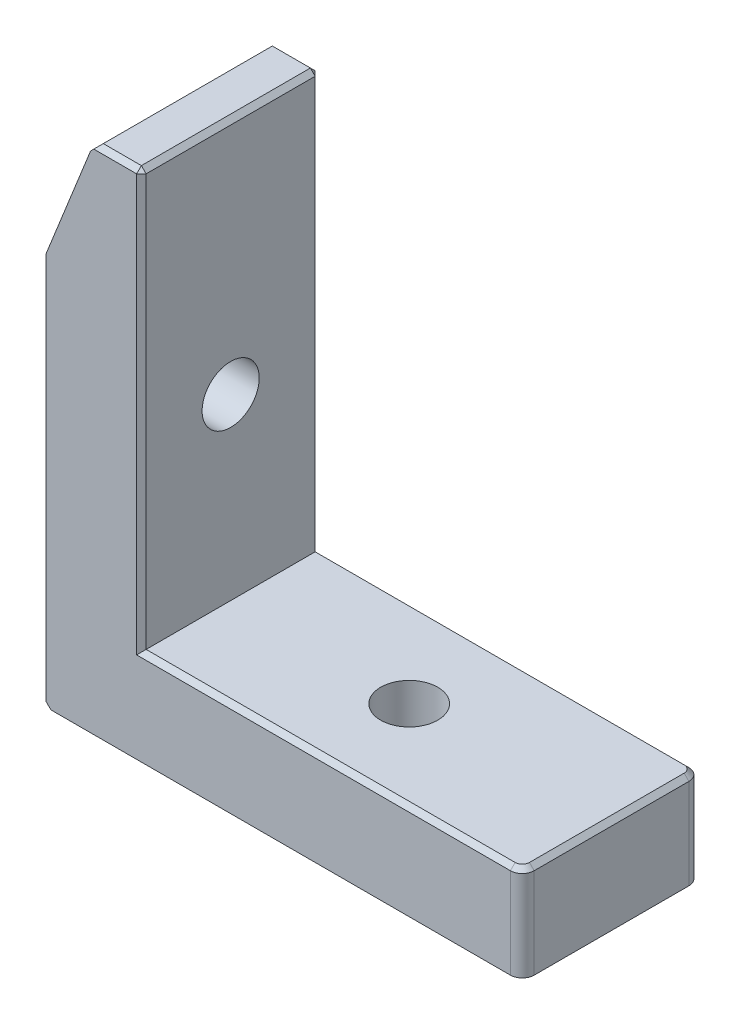
SolidWorks part; units mm, degrees
material "ABS"
ref_plane "Front Plane" through (0, 0, 0) normal (0, 0, 1) x (1, 0, 0)
ref_plane "Top Plane" through (0, 0, 0) normal (0, 1, 0) x (1, 0, 0)
ref_plane "Right Plane" through (0, 0, 0) normal (1, 0, 0) x (0, 0, -1)
sketch "Sketch1" plane through (0, 0, 0) normal (0, 0, 1) x (1, 0, 0)
  line L0 (0, 0) -> (0, 33)
  line L3 (4, 43) -> (8, 43)
  line L4 (8, 43) -> (8, 8)
  line L5 (8, 8) -> (40, 8)
  line L6 (40, 8) -> (40, 0)
  line L7 (40, 0) -> (0, 0)
  line L8 (0, 33) -> (4, 43)
  dimension "D1" = 35
  dimension "D2" = 8
  dimension "D3" = 4
  dimension "D4" = 8
  dimension "D5" = 40
  dimension "D6" = 10
extrude "Boss-Extrude1" add sketch "Sketch1" along normal mid plane 15
hole_wizard "CSK for M4 Hex Socket Countersunk Head Screw1" positions "Sketch2" profile "Sketch3" countersink size "M4" standard "DIN" end condition up to next
sketch "Sketch2" plane through (0, 0, 0) normal (0, -1, 0) x (-1, 0, 0)
  line L0 (-8, -7.5) -> (-8, 7.5) construction
  line L1 (0, 0) -> (-23, 0) construction
  line L2 (0, -7.5) -> (0, 7.5) construction
  point P0 (-23, 0)
  dimension "D1" = 15
sketch "Sketch3" plane through (23, 0, 0) normal (1, 0, 0) x (0, 0, -1)
  line L0 (0, 0) -> (0, 8)
  line L1 (0, 8) -> (2.4, 8)
  line L2 (2.4, 8) -> (2.4, 2.19)
  line L3 (2.4, 2.19) -> (4.59, 0)
  line L5 (4.59, 0) -> (0, 0)
  line L6 (-2.4, 2.19) -> (-4.59, 0) construction
  line L11 (0, -6.35) -> (0, 107.95) construction
  dimension "Thru Hole Dia." = 4.8
  dimension "Thru Hole Depth" = 8
  dimension "Near C'Sink Dia." = 9.18
  dimension "Near C'Sink Angle" = 90
hole_wizard "CSK for M4 Hex Socket Countersunk Head Screw2" positions "Sketch4" profile "Sketch5" countersink size "M4" standard "DIN" end condition up to next
sketch "Sketch4" plane through (0, 0, 0) normal (-1, 0, 0) x (0, 0, 1)
  line L0 (0, 0) -> (0, 23) construction
  line L2 (7.5, 8) -> (-7.5, 8) construction
  point P0 (0, 23)
  dimension "D1" = 15
sketch "Sketch5" plane through (0, 23, 0) normal (0, 1, 0) x (0, 0, 1)
  line L0 (0, 0) -> (0, 8)
  line L1 (0, 8) -> (2.4, 8)
  line L2 (2.4, 8) -> (2.4, 2.19)
  line L3 (2.4, 2.19) -> (4.59, 0)
  line L5 (4.59, 0) -> (0, 0)
  line L6 (-2.4, 2.19) -> (-4.59, 0) construction
  line L11 (0, -6.35) -> (0, 107.95) construction
  dimension "Thru Hole Dia." = 4.8
  dimension "Thru Hole Depth" = 8
  dimension "Near C'Sink Dia." = 9.18
  dimension "Near C'Sink Angle" = 90
fillet "Fillet1" radius 1 2 edges at (40, 4, -7.5) (40, 4, 7.5)
chamfer "Chamfer1" distance 0.4 angle 45 12 edges at (8, 43, 0) (0, 0, 0) (4, 43, 0) (6, 43, -7.5) (6, 43, 7.5) (40, 8, 0) (23.5, 8, -7.5) (23.5, 8, 7.5) (8, 25.5, -7.5) (8, 25.5, 7.5) (39.7071, 8, -7.2071) (39.7071, 8, 7.2071)
